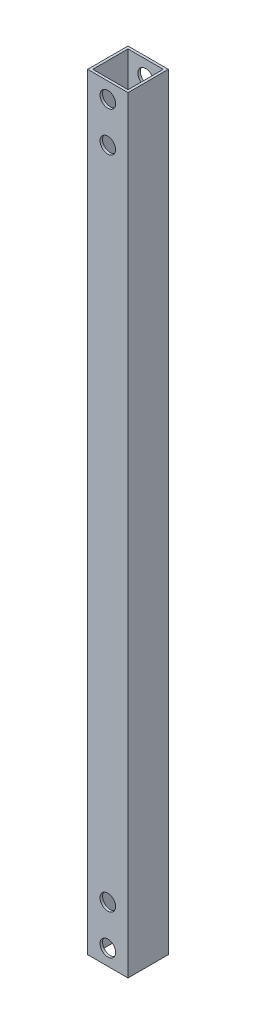
SolidWorks part; units mm, degrees
material "1060 Alloy"
ref_plane "Front Plane" through (0, 0, 0) normal (0, 0, 1) x (1, 0, 0)
ref_plane "Top Plane" through (0, 0, 0) normal (0, 1, 0) x (1, 0, 0)
ref_plane "Right Plane" through (0, 0, 0) normal (1, 0, 0) x (0, 0, -1)
sketch "Sketch1" plane through (0, 0, 0) normal (0, 1, 0) x (1, 0, 0)
  line L1 (-12.7, -12.7) -> (12.7, -12.7)
  line L2 (-12.7, -12.7) -> (-12.7, 12.7)
  line L3 (-12.7, 12.7) -> (12.7, 12.7)
  line L4 (12.7, -12.7) -> (12.7, 12.7)
  line L5 (-12.7, -12.7) -> (12.7, 12.7) construction
  line L6 (-12.7, 12.7) -> (12.7, -12.7) construction
  point P0 (0, 0)
  dimension "D1" = 25.4
extrude "Extrude-Thin1" add sketch "Sketch1" along normal blind 482.6 thin thin type one direction reverse wall 1.5875
sketch "Sketch2" plane through (0, 0, -12.7) normal (0, 0, -1) x (-1, 0, 0)
  line L0 (0, 482.6) -> (0, 0) construction
  line L1 (-12.7, 482.6) -> (12.7, 482.6) construction
  line L2 (-12.7, 0) -> (12.7, 0) construction
  line L3 (12.7, 241.3) -> (-12.7, 241.3) construction
  line L4 (12.7, 482.6) -> (12.7, 0) construction
  line L5 (-12.7, 482.6) -> (-12.7, 0) construction
  point P6 (0, 472.6)
  point P7 (0, 447.6)
  point P14 (0, 35)
  point P15 (0, 10)
  dimension "D1" = 10
  dimension "D2" = 25
hole_wizard "3/8 Clearance Hole1" positions "Sketch3" profile "Sketch4" hole size "3/8" standard "ANSI Inch" end condition through all
sketch "Sketch3" plane through (0, 0, -12.7) normal (0, 0, -1) x (-1, 0, 0)
  point P0 (0, 472.6)
  point P3 (0, 447.6)
  point P6 (0, 35)
  point P9 (0, 10)
sketch "Sketch4" plane through (0, 472.6, -12.7) normal (1, 0, 0) x (0, 1, 0)
  line L0 (0, 0) -> (0, 25.4)
  line L1 (0, 25.4) -> (4.9022, 25.4)
  line L2 (4.9022, 25.4) -> (4.9022, 0)
  line L5 (4.9022, 0) -> (0, 0)
  line L11 (0, -6.35) -> (0, 107.95) construction
  dimension "Thru Hole Dia." = 9.8044
  dimension "Thru Hole Depth" = 25.4
sketch "Sketch6" [suppressed] plane through (0, 0, -12.7) normal (0, 0, -1) x (-1, 0, 0)
  line L0 (12.7, 177.8) -> (-12.7, 177.8) construction
  line L1 (0, 355.6) -> (0, 0) construction
  point P0 (0, 190.3)
  point P1 (0, 165.3)
  dimension "D1" = 12.5
  dimension "D2" = 12.5
hole_wizard "M10 Clearance Hole2" [suppressed] positions "Sketch7" profile "Sketch8" hole size "M10" standard "ANSI Metric"
sketch "Sketch7" [suppressed] plane through (0, 0, -12.7) normal (0, 0, -1) x (-1, 0, 0)
  point P0 (0, 165.3)
  point P3 (0, 190.3)
sketch "Sketch8" plane through (0, 165.3, -12.7) normal (1, 0, 0) x (0, 1, 0)
  line L0 (0, 0) -> (0, 25.4)
  line L1 (0, 25.4) -> (5.5, 25.4)
  line L2 (5.5, 25.4) -> (5.5, 0.025)
  line L3 (5.5, 0.025) -> (5.525, 0)
  line L5 (5.525, 0) -> (0, 0)
  line L6 (-5.5, 0.025) -> (-5.525, 0) construction
  line L11 (0, -6.35) -> (0, 107.95) construction
  dimension "Thru Hole Dia." = 11
  dimension "Thru Hole Depth" = 25.4
  dimension "Near C'Sink Dia." = 11.05
  dimension "Near C'Sink Angle" = 90
pattern_linear "LPattern2" [suppressed] count 6 spacing 25 count 6 spacing 25
